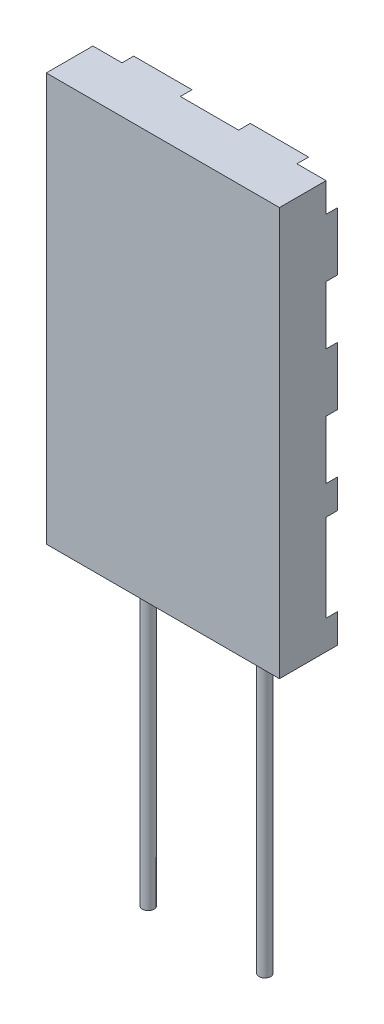
SolidWorks part; units mm, degrees
ref_plane "前视基准面" through (0, 0, 0) normal (0, 0, 1) x (1, 0, 0)
ref_plane "上视基准面" through (0, 0, 0) normal (0, 1, 0) x (1, 0, 0)
ref_plane "右视基准面" through (0, 0, 0) normal (1, 0, 0) x (0, 0, -1)
sketch "草图1" plane through (0, 0, 0) normal (0, 0, 1) x (1, 0, 0)
  line L1 (-2, 3.5) -> (2, 3.5)
  line L2 (-2, 3.5) -> (-2, -3.5)
  line L3 (-2, -3.5) -> (2, -3.5)
  line L4 (2, 3.5) -> (2, -3.5)
  line L5 (-2, 3.5) -> (2, -3.5) construction
  line L6 (-2, -3.5) -> (2, 3.5) construction
  point P0 (0, 0)
  dimension "D1" = 4
  dimension "D2" = 7
extrude "凸台-拉伸2" add sketch "草图1" along normal blind 1
sketch "草图2" plane through (0, 0, 0) normal (0, 0, -1) x (-1, 0, 0)
  line L0 (1, -3.5) -> (2, -2.5)
  line L1 (2, -3.5) -> (-2, -3.5) construction
  line L2 (2, 3.5) -> (2, -3.5) construction
  line L3 (0, -3.5) -> (2, -1.5)
  line L4 (-1, -3.5) -> (2, -0.5)
  line L5 (-2, -3.5) -> (2, 0.5)
  line L7 (-2, -2.5) -> (2, 1.5)
  line L8 (-2, -3.5) -> (-2, 3.5) construction
  line L9 (2, 4) -> (-2, 0)
  line L10 (2, 2.5) -> (-2, -1.5)
  line L11 (-2, -0.5) -> (2, 3.5)
  line L12 (-2, 1) -> (0.5, 3.5)
  line L13 (-2, 2) -> (-0.5, 3.5)
  line L14 (-2, 3.5) -> (2, 3.5) construction
  line L15 (-2, 3) -> (-1.5, 3.5)
  line L16 (2, -2.5) -> (2, -1.5)
  line L17 (2, -0.5) -> (2, 0.5)
  line L18 (2, 1.5) -> (2, 2.5)
  line L19 (2, 3.5) -> (2, 4)
  line L20 (0, -3.5) -> (1, -3.5)
  line L21 (-2, -3.5) -> (-1, -3.5)
  line L22 (-2, -2.5) -> (-2, -1.5)
  line L23 (-2, -0.5) -> (-2, 0)
  line L24 (-2, 1) -> (-2, 2)
  line L25 (-2, 3) -> (-2, 3.5)
  line L26 (-2, 3.5) -> (-1.5, 3.5)
  line L27 (-0.5, 3.5) -> (0.5, 3.5)
  dimension "D1" = 45
  dimension "D2" = 1
  dimension "D3" = 1
  dimension "D4" = 1
  dimension "D6" = 1
  dimension "D7" = 1
  dimension "D8" = 1
  dimension "D9" = 1
  dimension "D10" = 1
  dimension "D11" = 1
extrude "切除-拉伸1" cut sketch "草图2" against normal blind 0.2
sketch "草图4" plane through (0, 0, 0) normal (0, 0, 1) x (1, 0, 0)
  line L0 (1, -4) -> (2, -3)
  line L1 (0, -4) -> (2, -2)
  line L2 (-1, -4) -> (2, -1)
  line L3 (-2, -4) -> (2, 0)
  line L4 (-2, -3) -> (2, 1)
  line L5 (2, 4) -> (-2, 0)
  line L6 (2, 2) -> (-2, -2)
  line L7 (-2, -1) -> (2, 3)
  line L8 (-2, 1) -> (1, 4)
  line L9 (-2, 2) -> (0, 4)
  line L10 (-2, 3) -> (-1, 4)
  line L11 (2, -3) -> (2, -2)
  line L12 (2, -1) -> (2, 0)
  line L13 (2, 1) -> (2, 2)
  line L14 (2, 3) -> (2, 4)
  line L15 (0, -4) -> (1, -4)
  line L16 (-2, -4) -> (-1, -4)
  line L17 (-2, -3) -> (-2, -2)
  line L18 (-2, -1) -> (-2, 0)
  line L19 (-2, 1) -> (-2, 2)
  line L20 (-2, 3) -> (-2, 4)
  line L21 (-2, 4) -> (-1, 4)
  line L22 (0, 4) -> (1, 4)
extrude "切除-拉伸3" cut sketch "草图4" along normal blind 0.2
ref_plane "基准面4" through (0, 0, 0.5) normal (0, 0, 1) x (1, 0, 0)
sketch "草图5" plane through (0, 0, 0.5) normal (0, 0, 1) x (1, 0, 0)
  line L2 (1.25, -3.5) -> (1.25, -8.5)
  line L3 (2, -3.5) -> (0.5, -3.5) construction
  dimension "D1" = 5
sweep "扫描1" add path "草图5" circular profile diameter 0.2 parameters "D3"=0.2
sketch "草图18" plane through (0, 0, 0.5) normal (0, 0, 1) x (1, 0, 0)
  line L0 (-0.75, -3.5) -> (-0.75, -8.5)
  line L1 (0, -3.5) -> (-1.5, -3.5) construction
  dimension "D1" = 5
sweep "扫描2" add path "草图18" circular profile diameter 0.2 parameters "D3"=0.2
